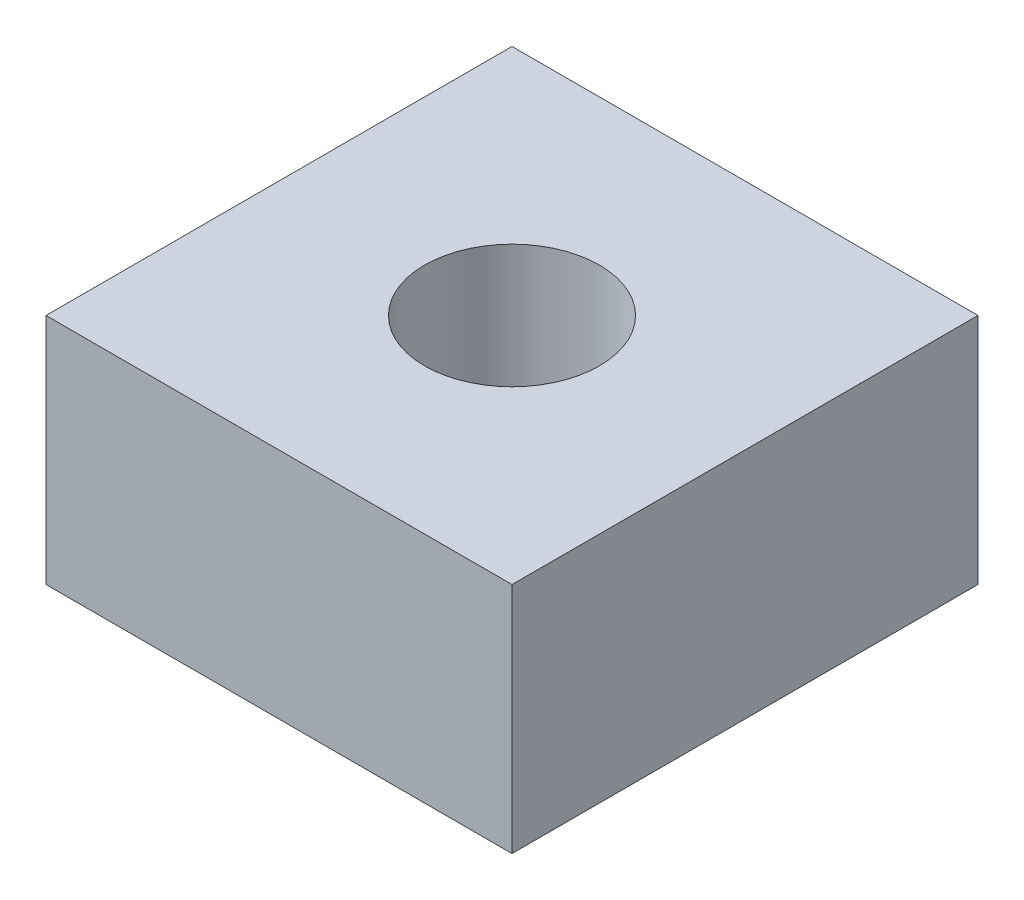
SolidWorks part; units mm, degrees
ref_plane "Front Plane" through (0, 0, 0) normal (0, 0, 1) x (1, 0, 0)
ref_plane "Top Plane" through (0, 0, 0) normal (0, 1, 0) x (1, 0, 0)
ref_plane "Right Plane" through (0, 0, 0) normal (1, 0, 0) x (0, 0, -1)
sketch "Sketch1" plane through (0, 0, 0) normal (0, 1, 0) x (1, 0, 0)
  line L1 (-12.7, -12.7) -> (12.7, -12.7)
  line L2 (-12.7, -12.7) -> (-12.7, 12.7)
  line L3 (-12.7, 12.7) -> (12.7, 12.7)
  line L4 (12.7, -12.7) -> (12.7, 12.7)
  line L5 (-12.7, -12.7) -> (12.7, 12.7) construction
  line L6 (-12.7, 12.7) -> (12.7, -12.7) construction
  circle A0 centre (0, 0) radius 4.7625
  point P0 (0, 0)
  dimension "D2" = 9.525
  dimension "D1" = 25.4
extrude "Boss-Extrude1" add sketch "Sketch1" along normal blind 12.7
